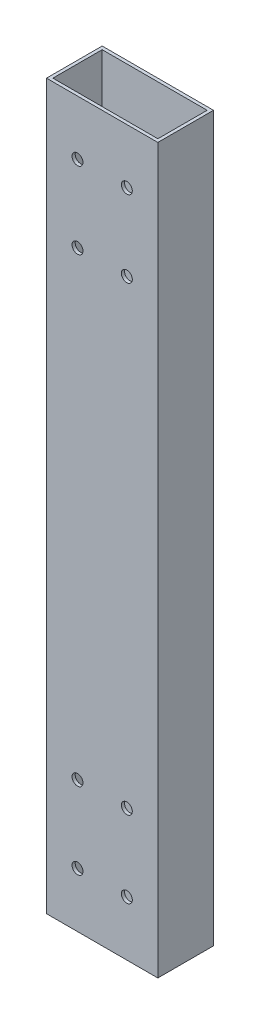
SolidWorks part; units mm, degrees
material "Thornel VCB-20 Carbon Cloth"
ref_plane "Front Plane" through (0, 0, 0) normal (0, 0, 1) x (1, 0, 0)
ref_plane "Top Plane" through (0, 0, 0) normal (0, 1, 0) x (1, 0, 0)
ref_plane "Right Plane" through (0, 0, 0) normal (1, 0, 0) x (0, 0, -1)
sketch "Sketch1" plane through (0, 0, 0) normal (0, 1, 0) x (1, 0, 0)
  line L0 (-25.4, 0) -> (-28.575, 0) construction
  line L1 (-25.4, -12.7) -> (25.4, -12.7)
  line L2 (-25.4, -12.7) -> (-25.4, 12.7)
  line L3 (-25.4, 12.7) -> (25.4, 12.7)
  line L4 (25.4, -12.7) -> (25.4, 12.7)
  line L5 (-25.4, -12.7) -> (25.4, 12.7) construction
  line L6 (-25.4, 12.7) -> (25.4, -12.7) construction
  line L11 (-23.95, 11.25) -> (23.95, 11.25)
  line L12 (23.95, -11.25) -> (23.95, 11.25)
  line L13 (0, -12.7) -> (0, -15.875) construction
  line L14 (-23.95, -11.25) -> (23.95, -11.25)
  line L15 (-23.95, -11.25) -> (-23.95, 11.25)
  point P0 (0, 0)
  point P6 (0, 0)
  dimension "D1" = 25.4
  dimension "D2" = 50.8
  dimension "D3" = 1.45
extrude "Boss-Extrude1" add sketch "Sketch1" along normal blind 330.2
sketch "Sketch2" plane through (0, 0, 12.7) normal (0, 0, 1) x (1, 0, 0)
  line L1 (-11.25, 25) -> (11.25, 25) construction
  line L2 (-11.25, 25) -> (-11.25, 60) construction
  line L3 (-11.25, 60) -> (11.25, 60) construction
  line L4 (11.25, 25) -> (11.25, 60) construction
  circle A0 centre (-11.25, 60) radius 2.5
  circle A1 centre (-11.25, 25) radius 2.5
  circle A2 centre (11.25, 25) radius 2.5
  circle A3 centre (11.25, 60) radius 2.5
  point P4 (0, 25)
  dimension "D4" = 5
  dimension "D1" = 22.5
  dimension "D2" = 35
  dimension "D3" = 25
extrude "Cut-Extrude1" cut sketch "Sketch2" against normal through all contours A3 | A0 | A1 | A2
ref_plane "Plane1" through (0, 165.1, 0) normal (0, 1, 0) x (1, 0, 0)
mirror "Mirror1" about plane through (0, 165.1, 0) normal (0, 1, 0) of "Cut-Extrude1"
equation "\"tube_width\"= 1in"
equation "\"tube_height\"= 2in"
equation "\"tube_thickness\"= 0.125in"
equation "\"tube_length\"= 1.5ft"
equation "\"D1@Boss-Extrude1\"=\"tube_length\""
equation "\"D1@Sketch1\"=\"tube_width\""
equation "\"D2@Sketch1\"=\"tube_height\""
